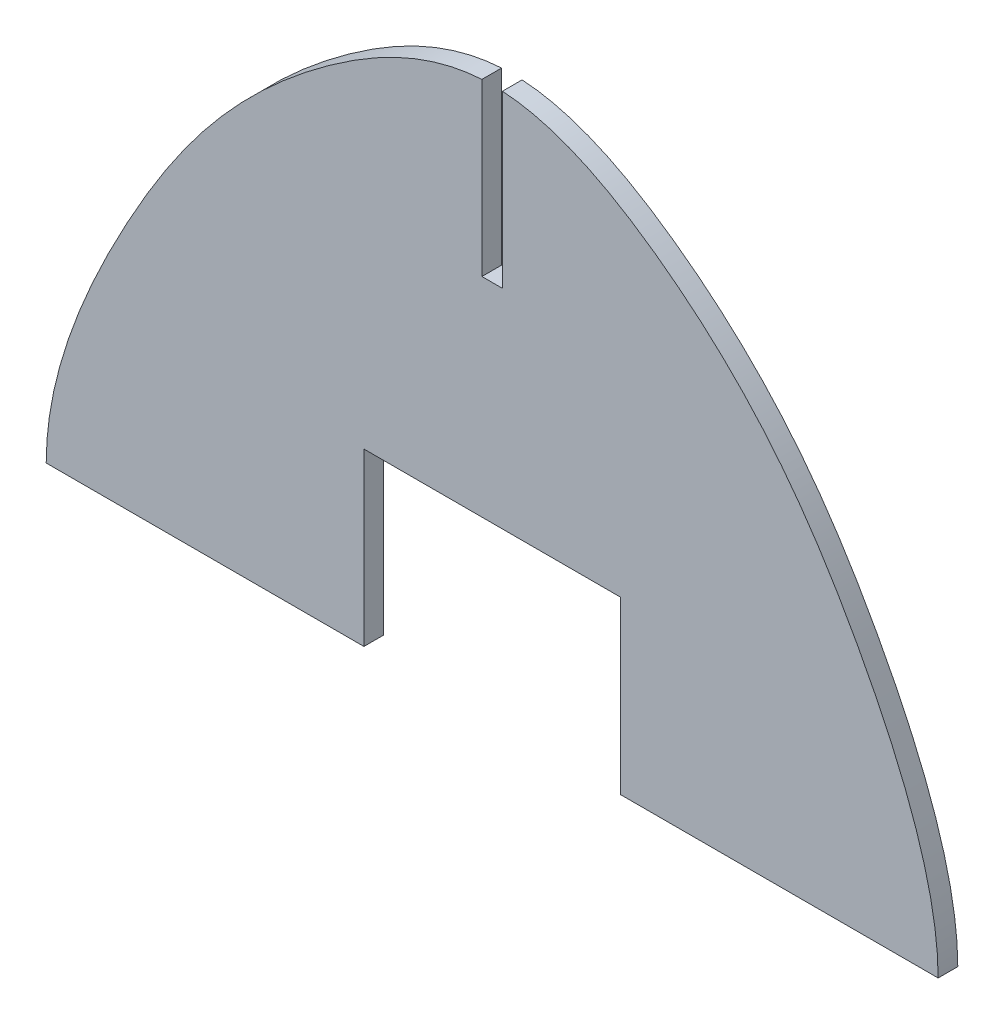
SolidWorks part; units mm, degrees
ref_plane "Front" through (0, 0, 0) normal (0, 0, 1) x (1, 0, 0)
ref_plane "Top" through (0, 0, 0) normal (0, 1, 0) x (1, 0, 0)
ref_plane "Right" through (0, 0, 0) normal (1, 0, 0) x (0, 0, -1)
sketch "Sketch1" plane through (0, 0, 0) normal (0, 0, 1) x (1, 0, 0)
  line L1 (0, 203.2) -> (33.1368, 203.2) construction
  line L2 (132.4891, 39.6875) -> (132.4891, 77.7824) construction
  spline S0 degree 3 poles (0, 203.2) (17.2354, 203.2) (50.0612, 185.9213) (85.2182, 152.2019) (115.2062, 104.3662) (132.4891, 63.291) (132.4891, 39.6875) knots 0 0 0 0 0.231796 0.463576 0.653722 1 1 1 1
sketch "Sketch2" plane through (0, 0, 0) normal (0, 0, 1) x (1, 0, 0)
  line L0 (132.4891, 39.6875) -> (0, 39.6875)
  line L1 (0, 39.6875) -> (0, 203.2)
  spline S0 degree 3 poles (-68.1516, -3778.5859) (-322.7979, 241.4962) (-39.9695, 272.2705) (85.2182, 152.2019) (200.1834, -31.186) (212.5336, -396.4357) (-3583.3633, 1457.4917) knots -1.674062 -1.674062 -1.674062 -1.674062 0.231796 0.463576 0.653722 3.176865 3.176865 3.176865 3.176865 only from (0, 203.2) to (132.4891, 39.6875) construction
  spline S1 degree 3 poles (0, 203.2) (17.2354, 203.2) (50.0612, 185.9213) (85.2182, 152.2019) (115.2062, 104.3662) (132.4891, 63.291) (132.4891, 39.6875) knots 0 0 0 0 0.231796 0.463576 0.653722 1 1 1 1
extrude "Boss-Extrude1" add sketch "Sketch2" along normal blind 5.842
sketch "Sketch3" plane through (0, 0, 5.842) normal (0, 0, 1) x (1, 0, 0)
  line L1 (0, 39.6875) -> (38.1, 39.6875)
  line L2 (0, 39.6875) -> (0, 90.4875)
  line L3 (0, 90.4875) -> (38.1, 90.4875)
  line L4 (38.1, 39.6875) -> (38.1, 90.4875)
  line L5 (0, 203.2) -> (3.048, 203.2)
  line L6 (0, 203.2) -> (0, 152.4)
  line L7 (0, 152.4) -> (3.048, 152.4)
  line L8 (3.048, 203.2) -> (3.048, 152.4)
  dimension "D1" = 38.1
  dimension "D2" = 50.8
  dimension "D3" = 50.8
  dimension "D4" = 3.048
extrude "Cut-Extrude1" cut sketch "Sketch3" against normal through all
mirror "Mirror1" about plane through (0, 0, 0) normal (1, 0, 0) of bodies 102
